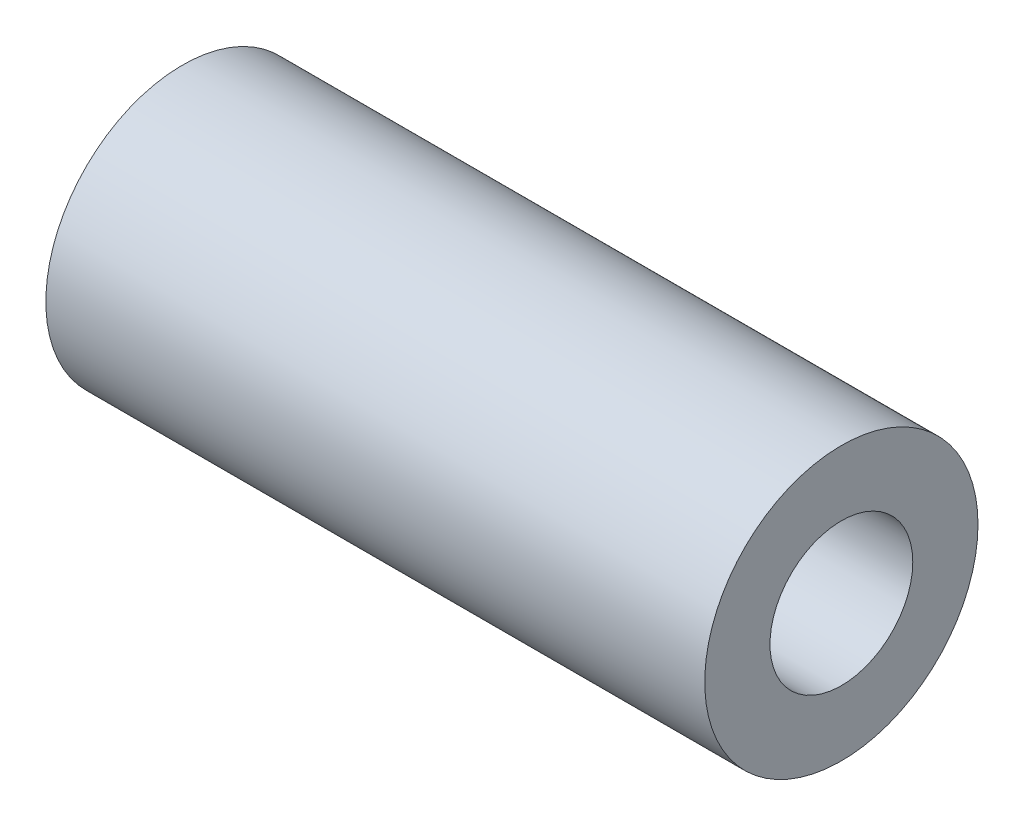
SolidWorks part; units mm, degrees
material "6061-T6 (SS)"
ref_plane "Front Plane" through (0, 0, 0) normal (0, 0, 1) x (1, 0, 0)
ref_plane "Top Plane" through (0, 0, 0) normal (0, 1, 0) x (1, 0, 0)
ref_plane "Right Plane" through (0, 0, 0) normal (1, 0, 0) x (0, 0, -1)
sketch "Sketch1" plane through (0, 0, 0) normal (1, 0, 0) x (0, 0, -1)
  circle A0 centre (0, 0) radius 2.4892
  circle A1 centre (0, 0) radius 4.7625
  dimension "D1" = 4.9784
  dimension "D2" = 9.525
extrude "Boss-Extrude1" add sketch "Sketch1" along normal mid plane 22.968
